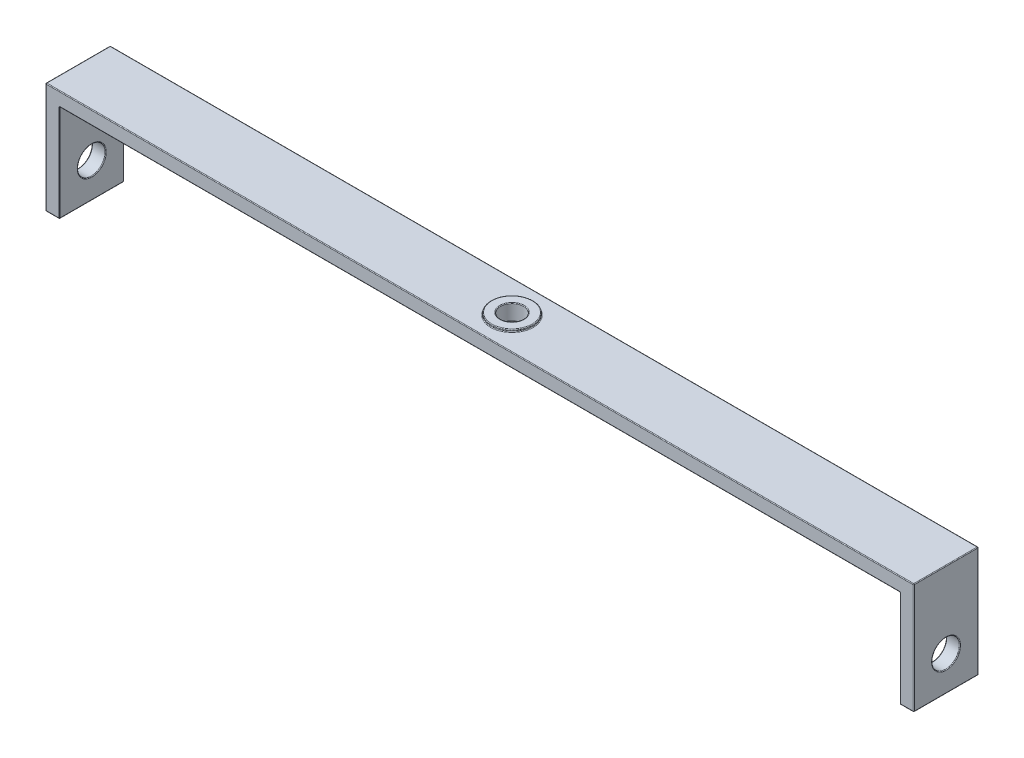
SolidWorks part; units mm, degrees
ref_plane "Front Plane" through (0, 0, 0) normal (0, 0, 1) x (1, 0, 0)
ref_plane "Top Plane" through (0, 0, 0) normal (0, 1, 0) x (1, 0, 0)
ref_plane "Right Plane" through (0, 0, 0) normal (1, 0, 0) x (0, 0, -1)
sketch "Sketch1" plane through (0, 0, 0) normal (0, 0, 1) x (1, 0, 0)
  line L0 (-47, -12) -> (-47, 0)
  line L1 (-47, 0) -> (47, 0)
  line L2 (47, 0) -> (47, -12)
  line L3 (-45.5, -12) -> (-45.5, -1.5)
  line L4 (-45.5, -1.5) -> (45.5, -1.5)
  line L5 (45.5, -1.5) -> (45.5, -12)
  line L6 (-47, -12) -> (-45.5, -12)
  line L7 (45.5, -12) -> (47, -12)
  point P2 (0, 0)
  dimension "D1" = 94
  dimension "D2" = 12
  dimension "D3" = 1.5
extrude "Boss-Extrude1" add sketch "Sketch1" along normal mid plane 7
sketch "Sketch2" plane through (0, 0, 0) normal (0, 1, 0) x (1, 0, 0)
  circle A0 centre (0, 0) radius 1.25
  dimension "D1" = 2.5
extrude "Cut-Extrude1" cut sketch "Sketch2" against normal through all
sketch "Sketch3" plane through (0, 0, 0) normal (0, 1, 0) x (1, 0, 0)
  circle A0 centre (0, 0) radius 1.25 construction
  circle A1 centre (0, 0) radius 1.25
  circle A2 centre (0, 0) radius 2.25
  dimension "D1" = 1
extrude "Boss-Extrude2" add sketch "Sketch3" along normal mid plane 0.5
sketch "Sketch4" plane through (0, 0, 0) normal (1, 0, 0) x (0, 0, -1)
  line L0 (0, 0.25) -> (0, -8.25) construction
  line L1 (1.25, 0.25) -> (-1.25, 0.25) construction
  circle A0 centre (0, -8.25) radius 1.5
  dimension "D2" = 3
  dimension "D1" = 8.5
extrude "Cut-Extrude2" cut sketch "Sketch4" against normal through all both and the other way through all
fillet "Fillet1" radius 0.075 32 edges at (47, -8.25, -1.5) (-47, -8.25, -1.5) (45.5, -8.25, -1.5) (-45.5, -8.25, 1.5) (-1.25, 0.25, 0) (-2.25, 0.25, 0) (0, -1.5, 1.25) (-46.25, -12, -3.5) (-45.5, -6.75, -3.5) (0, -1.5, -3.5) (45.5, -6.75, -3.5) (46.25, -12, -3.5) (47, -6, -3.5) (0, 0, -3.5) (-47, -6, -3.5) (-46.25, -12, 3.5) (-45.5, -6.75, 3.5) (0, -1.5, 3.5) (45.5, -6.75, 3.5) (46.25, -12, 3.5) (47, -6, 3.5) (-47, -6, 3.5) (-47, -12, 0) (-47, 0, 0) (47, 0, 0) (47, -12, 0) (45.5, -12, 0) (45.5, -1.5, 0) (-45.5, -1.5, 0) (-45.5, -12, 0) (2.25, 0, 0) (0, 0, 3.5)
